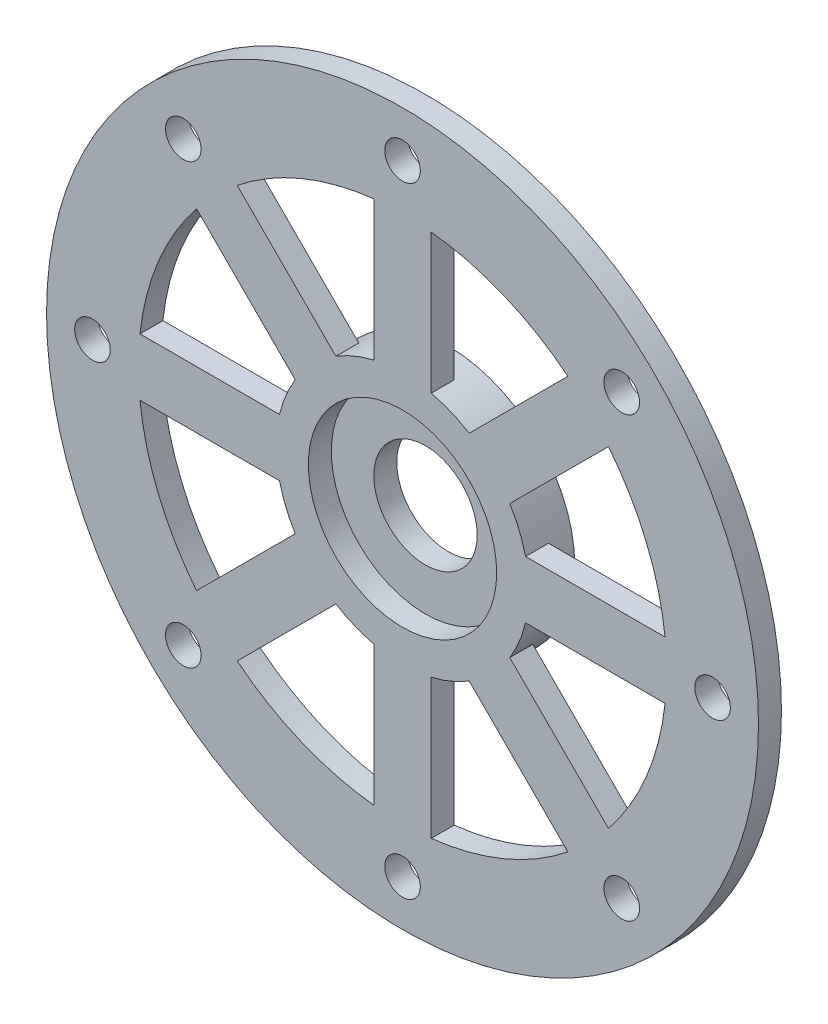
SolidWorks part; units mm, degrees
ref_plane "Front Plane" through (0, 0, 0) normal (0, 0, 1) x (1, 0, 0)
ref_plane "Top Plane" through (0, 0, 0) normal (0, 1, 0) x (1, 0, 0)
ref_plane "Right Plane" through (0, 0, 0) normal (1, 0, 0) x (0, 0, -1)
sketch "Sketch1" plane through (0, 0, 0) normal (0, 0, 1) x (1, 0, 0)
  line L0 (0, 0) -> (-27, 0) construction
  line L1 (-11, -2.5) -> (-11, 2.5) construction
  line L2 (-10.7121, 2.5) -> (-22.8637, 2.5)
  line L3 (-10.7121, -2.5) -> (-22.8637, -2.5)
  line L4 (-5.8069, 9.3424) -> (-14.3993, 17.9349)
  line L5 (-9.3424, 5.8069) -> (-17.9349, 14.3993)
  line L6 (2.5, 10.7121) -> (2.5, 22.8637)
  line L7 (-2.5, 10.7121) -> (-2.5, 22.8637)
  line L8 (9.3424, 5.8069) -> (17.9349, 14.3993)
  line L9 (5.8069, 9.3424) -> (14.3993, 17.9349)
  line L10 (10.7121, -2.5) -> (22.8637, -2.5)
  line L11 (10.7121, 2.5) -> (22.8637, 2.5)
  line L12 (5.8069, -9.3424) -> (14.3993, -17.9349)
  line L13 (9.3424, -5.8069) -> (17.9349, -14.3993)
  line L14 (-2.5, -10.7121) -> (-2.5, -22.8637)
  line L15 (2.5, -10.7121) -> (2.5, -22.8637)
  line L16 (-9.3424, -5.8069) -> (-17.9349, -14.3993)
  line L17 (-5.8069, -9.3424) -> (-14.3993, -17.9349)
  circle A0 centre (0, 0) radius 31
  circle A1 centre (-27, 0) radius 1.55
  circle A2 centre (-19.0919, 19.0919) radius 1.55
  circle A3 centre (0, 27) radius 1.55
  circle A4 centre (19.0919, 19.0919) radius 1.55
  circle A5 centre (27, 0) radius 1.55
  circle A6 centre (19.0919, -19.0919) radius 1.55
  circle A7 centre (0, -27) radius 1.55
  circle A8 centre (-19.0919, -19.0919) radius 1.55
  arc A9 (-22.8637, -2.5) -> (-17.9349, -14.3993) centre (0, 0) ccw
  arc A10 (-10.7121, -2.5) -> (-9.3424, -5.8069) centre (0, 0) ccw
  arc A11 (-17.9349, 14.3993) -> (-22.8637, 2.5) centre (0, 0) ccw
  arc A12 (-9.3424, 5.8069) -> (-10.7121, 2.5) centre (0, 0) ccw
  arc A13 (-2.5, 10.7121) -> (-5.8069, 9.3424) centre (0, 0) ccw
  arc A14 (-2.5, 22.8637) -> (-14.3993, 17.9349) centre (0, 0) ccw
  arc A15 (14.3993, 17.9349) -> (2.5, 22.8637) centre (0, 0) ccw
  arc A16 (5.8069, 9.3424) -> (2.5, 10.7121) centre (0, 0) ccw
  arc A17 (10.7121, 2.5) -> (9.3424, 5.8069) centre (0, 0) ccw
  arc A18 (9.3424, -5.8069) -> (10.7121, -2.5) centre (0, 0) ccw
  arc A19 (2.5, -10.7121) -> (5.8069, -9.3424) centre (0, 0) ccw
  arc A20 (-5.8069, -9.3424) -> (-2.5, -10.7121) centre (0, 0) ccw
  arc A21 (22.8637, 2.5) -> (17.9349, 14.3993) centre (0, 0) ccw
  arc A22 (17.9349, -14.3993) -> (22.8637, -2.5) centre (0, 0) ccw
  arc A23 (2.5, -22.8637) -> (14.3993, -17.9349) centre (0, 0) ccw
  arc A24 (-14.3993, -17.9349) -> (-2.5, -22.8637) centre (0, 0) ccw
  point P21 (0, 0)
  point P25 (-11, 0)
  point P57 (0, 0)
  dimension "D1" = 8
  dimension "D2" = 8
extrude "Boss-Extrude1" add sketch "Sketch1" along normal blind 2
sketch "Sketch3" plane through (0, 0, 0) normal (0, 0, -1) x (-1, 0, 0)
  circle A0 centre (0, 0) radius 11
extrude "Boss-Extrude2" add sketch "Sketch3" along normal blind 2
sketch "Sketch4" plane through (0, 0, 2) normal (0, 0, 1) x (1, 0, 0)
  circle A0 centre (0, 0) radius 4.5
extrude "Cut-Extrude2" cut sketch "Sketch4" against normal up to surface (4 mm away) up to face at (-11, 0, -2)
sketch "Sketch2" plane through (0, 0, 2) normal (0, 0, 1) x (1, 0, 0)
  circle A0 centre (0, 0) radius 8.2
extrude "Cut-Extrude1" cut sketch "Sketch2" against normal blind 2
